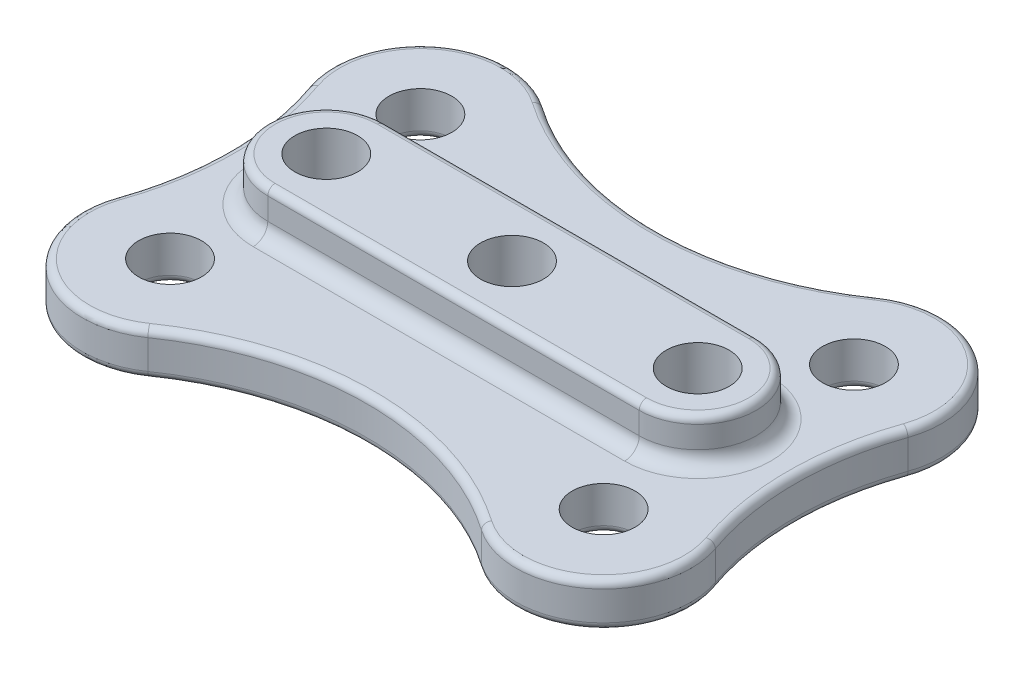
SolidWorks part; units mm, degrees
ref_plane "Front Plane" through (0, 0, 0) normal (0, 0, 1) x (1, 0, 0)
ref_plane "Top Plane" through (0, 0, 0) normal (0, 1, 0) x (1, 0, 0)
ref_plane "Right Plane" through (0, 0, 0) normal (1, 0, 0) x (0, 0, -1)
sketch "Sketch1" plane through (0, 0, 0) normal (0, 1, 0) x (1, 0, 0)
  line L0 (-11.2381, 13.3691) -> (2.391, 3.2067) construction
  line L1 (-20.8247, -14.559) -> (20.8247, -14.559) construction
  line L2 (-20.8247, -14.559) -> (-20.8247, 14.559) construction
  line L3 (-20.8247, 14.559) -> (20.8247, 14.559) construction
  line L4 (20.8247, -14.559) -> (20.8247, 14.559) construction
  line L5 (-20.8247, -14.559) -> (20.8247, 14.559) construction
  line L6 (-20.8247, 14.559) -> (20.8247, -14.559) construction
  line L7 (-2.391, 3.2067) -> (11.2381, 13.3691) construction
  line L8 (-20.1684, 5.8305) -> (-16.2625, -1.819) construction
  line L9 (-16.2625, 1.819) -> (-20.1684, -5.8305) construction
  line L10 (-11.2381, -13.3691) -> (2.391, -3.2067) construction
  line L11 (-2.391, -3.2067) -> (11.2381, -13.3691) construction
  line L12 (20.1684, -5.8305) -> (16.2625, 1.819) construction
  line L13 (16.2625, -1.819) -> (20.1684, 5.8305) construction
  line L14 (-11.2381, 13.3691) -> (0, 4.9895)
  line L15 (0, 4.9895) -> (11.2381, 13.3691)
  line L16 (20.1684, 5.8305) -> (17.1913, 0)
  line L17 (17.1913, 0) -> (20.1684, -5.8305)
  line L18 (11.2381, -13.3691) -> (0, -4.9895)
  line L19 (0, -4.9895) -> (-11.2381, -13.3691)
  line L20 (-20.1684, 5.8305) -> (-17.1913, 0)
  line L21 (-17.1913, 0) -> (-20.1684, -5.8305)
  circle A0 centre (0, 0) radius 17.1181 construction
  circle A2 centre (0, 0) radius 2.15
  circle A3 centre (14.8247, 8.559) radius 2.15
  circle A4 centre (14.8247, -8.559) radius 2.15
  circle A6 centre (-14.8247, -8.559) radius 2.15
  circle A7 centre (-14.8247, 8.559) radius 2.15
  circle A8 centre (12.7, 0) radius 2.15
  circle A9 centre (-12.7, 0) radius 2.15
  arc A10 (-11.2381, 13.3691) -> (-20.1684, 5.8305) centre (-14.8247, 8.559) ccw
  circle A11 centre (0, 0) radius 4 construction
  arc A12 (-20.1684, -5.8305) -> (-11.2381, -13.3691) centre (-14.8247, -8.559) ccw
  arc A13 (11.2381, -13.3691) -> (20.1684, -5.8305) centre (14.8247, -8.559) ccw
  arc A14 (20.1684, 5.8305) -> (11.2381, 13.3691) centre (14.8247, 8.559) ccw
  circle A15 centre (12.7, 0) radius 4 construction
  circle A16 centre (-12.7, 0) radius 4 construction
  point P43 (-17.1913, 0)
  point P44 (0, 4.9895)
  point P45 (17.1913, 0)
  point P46 (0, -4.9895)
  dimension "D1" = 34.2361
  dimension "D2" = 6
  dimension "D3" = 4.3
  dimension "D6" = 4.3
  dimension "D7" = 8
  dimension "D5" = 12.7
  dimension "D4" = 6
extrude "Boss-Extrude1" add sketch "Sketch1" along normal blind 3
fillet "Fillet1" radius 20 4 edges at (17.1913, 1.5, 0) (-17.1913, 1.5, 0) (0, 1.5, 4.9895) (0, 1.5, -4.9895)
sketch "Sketch2" plane through (0, 3, 0) normal (0, 1, 0) x (1, 0, 0)
  line L0 (-12.7, 0) -> (12.7, 0) construction
  line L1 (-12.7, 4) -> (12.7, 4)
  line L2 (-12.7, -4) -> (12.7, -4)
  arc A0 (-12.7, 4) -> (-12.7, -4) centre (-12.7, 0) ccw
  arc A1 (12.7, -4) -> (12.7, 4) centre (12.7, 0) ccw
  circle A2 centre (12.7, 0) radius 2.15 construction
  circle A3 centre (0, 0) radius 2.15 construction
  circle A4 centre (-12.7, 0) radius 2.15 construction
  circle A5 centre (12.7, 0) radius 2.15
  circle A6 centre (0, 0) radius 2.15
  circle A7 centre (-12.7, 0) radius 2.15
  arc A8 (-20.4903, -6.5839) -> (-20.4903, 6.5839) centre (-39.3755, 0) ccw
  arc A9 (-20.4903, -6.5839) -> (-11.4036, -13.4882) centre (-14.8247, -8.559) ccw
  arc A10 (11.4036, -13.4882) -> (-11.4036, -13.4882) centre (0, -29.9185) ccw
  arc A11 (11.4036, -13.4882) -> (20.4903, -6.5839) centre (14.8247, -8.559) ccw
  arc A12 (20.4903, 6.5839) -> (20.4903, -6.5839) centre (39.3755, 0) ccw
  arc A13 (20.4903, 6.5839) -> (11.4036, 13.4882) centre (14.8247, 8.559) ccw
  arc A14 (-11.4036, 13.4882) -> (11.4036, 13.4882) centre (0, 29.9185) ccw
  arc A15 (-11.4036, 13.4882) -> (-20.4903, 6.5839) centre (-14.8247, 8.559) ccw
  arc A16 (-20.4903, -6.5839) -> (-20.4903, 6.5839) centre (-39.3755, 0) ccw
  arc A17 (-20.4903, -6.5839) -> (-11.4036, -13.4882) centre (-14.8247, -8.559) ccw
  arc A18 (11.4036, -13.4882) -> (-11.4036, -13.4882) centre (0, -29.9185) ccw
  arc A19 (11.4036, -13.4882) -> (20.4903, -6.5839) centre (14.8247, -8.559) ccw
  arc A20 (20.4903, 6.5839) -> (20.4903, -6.5839) centre (39.3755, 0) ccw
  arc A21 (20.4903, 6.5839) -> (11.4036, 13.4882) centre (14.8247, 8.559) ccw
  arc A22 (-11.4036, 13.4882) -> (11.4036, 13.4882) centre (0, 29.9185) ccw
  arc A23 (-11.4036, 13.4882) -> (-20.4903, 6.5839) centre (-14.8247, 8.559) ccw
  point P12 (0, 0)
  dimension "D2" = 8
  dimension "D1" = 0
extrude "Boss-Extrude2" add sketch "Sketch2" along normal blind 3
fillet "Fillet2" radius 0.5 27 edges at (-12.7, 0, 2.15) (-14.8247, 0, -6.409) (-14.8247, 0, 10.709) (14.8247, 0, 10.709) (14.8247, 0, -6.409) (12.7, 0, 2.15) (0, 0, 2.15) (-18.4547, 0, 13.3364) (0, 0, 9.9185) (18.4547, 0, 13.3364) (19.3755, 0, 0) (18.4547, 0, -13.3364) (0, 0, -9.9185) (-18.4547, 0, -13.3364) (-19.3755, 0, 0) (0, 3, -9.9185) (18.4547, 3, -13.3364) (19.3755, 3, 0) (18.4547, 3, 13.3364) (0, 3, 9.9185) (-18.4547, 3, 13.3364) (-19.3755, 3, 0) (-18.4547, 3, -13.3364) (-16.7, 6, 0) (0, 6, -4) (16.7, 6, 0) (0, 6, 4)
fillet "Fillet3" radius 1 4 edges at (-16.7, 3, 0) (0, 3, -4) (16.7, 3, 0) (0, 3, 4)
